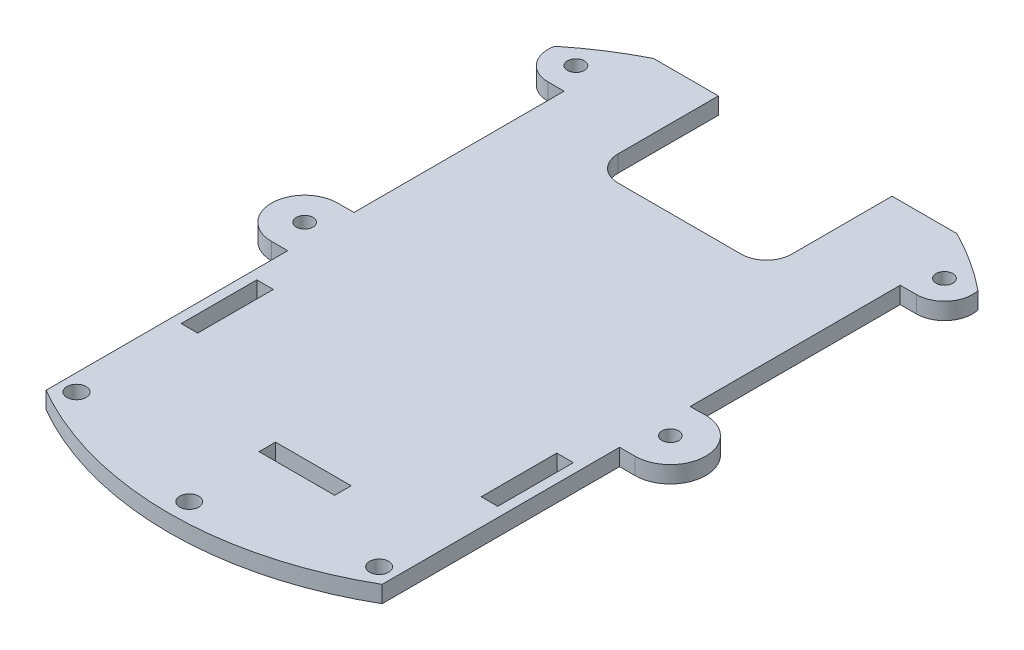
SolidWorks part; units mm, degrees
ref_plane "Alzado" through (0, 0, 0) normal (0, 0, 1) x (1, 0, 0)
ref_plane "Planta" through (0, 0, 0) normal (0, 1, 0) x (1, 0, 0)
ref_plane "Vista lateral" through (0, 0, 0) normal (1, 0, 0) x (0, 0, -1)
sketch "Croquis1" plane through (0, 0, 0) normal (0, 1, 0) x (1, 0, 0)
  line L0 (0, -45) -> (0, -62.5052) construction
  line L2 (-30, -38.4717) -> (-30, 4.6696)
  line L4 (30, -38.4717) -> (30, 3.903)
  line L5 (-30, -45) -> (30, 45) construction
  line L6 (-30, 45) -> (30, -45) construction
  line L8 (-27.0683, 67.0371) -> (-15.4924, 67.0371)
  line L9 (-32.892, 54) -> (-30, 54)
  line L10 (-30, 45) -> (-30, 54)
  line L11 (30, 45) -> (30, 54)
  line L12 (-32.892, 59) -> (-32.892, -85.621) construction
  line L13 (-15.4924, 55.619) -> (-15.4924, 67.0371)
  line L14 (15.5076, 55.6316) -> (15.5076, 67.0371)
  line L15 (15.5076, 67.0371) -> (27.0683, 67.0371)
  line L16 (-32.892, 10.5842) -> (-0.4332, 10.5842) construction
  line L17 (30, 54) -> (32.89, 54)
  line L18 (-0.4332, -33.1755) -> (-0.4332, 12.6245) construction
  line L19 (-10.9924, 44.6131) -> (11.0076, 44.6131)
  line L20 (15.5076, 49.1131) -> (15.5076, 55.6316)
  line L21 (-15.4924, 55.619) -> (-15.4924, 49.1131)
  line L22 (-32.892, 16.4988) -> (-30, 16.4988)
  line L23 (-32.892, 4.6696) -> (-30, 4.6696)
  line L24 (32.75, 10.2241) -> (0.4332, 10.5842) construction
  line L25 (32.75, 16.5451) -> (30, 16.4988)
  line L26 (32.75, 3.903) -> (30, 3.903)
  line L27 (-30, 16.4988) -> (-30, 45)
  line L28 (30, 16.4988) -> (30, 45)
  line L29 (-25.3, -2.597) -> (-28.25, -2.597)
  line L30 (25.3, -16.097) -> (28.25, -16.097)
  line L31 (25.3, -16.097) -> (25.3, -2.597)
  line L32 (25.3, -2.597) -> (28.25, -2.597)
  line L33 (28.25, -16.097) -> (28.25, -2.597)
  line L34 (25.3, -16.097) -> (28.25, -2.597) construction
  line L35 (25.3, -2.597) -> (28.25, -16.097) construction
  line L36 (-28.25, -16.097) -> (-28.25, -2.597)
  line L37 (-25.3, -16.097) -> (-28.25, -16.097)
  line L38 (-25.3, -16.097) -> (-25.3, -2.597)
  line L39 (12, -28.95) -> (-1.5, -28.95)
  line L40 (12, -28.95) -> (12, -26)
  line L41 (12, -26) -> (-1.5, -26)
  line L42 (-1.5, -28.95) -> (-1.5, -26)
  line L43 (12, -28.95) -> (-1.5, -26) construction
  line L44 (12, -26) -> (-1.5, -28.95) construction
  circle A0 centre (0, 13.4898) radius 60 construction
  arc A1 (-30, -38.4717) -> (30, -38.4717) centre (0, 13.4898) ccw
  arc A2 (-37.7667, 60.1125) -> (-32.892, 54) centre (-32.892, 59) ccw
  arc A3 (32.89, 54) -> (37.7642, 60.1145) centre (32.89, 59) ccw
  arc A4 (59.5975, 20.4278) -> (-59.5975, 20.4278) centre (0, 13.4898) ccw construction
  arc A5 (37.7642, 60.1145) -> (27.0683, 67.0371) centre (0, 13.4898) ccw
  arc A6 (-27.0683, 67.0371) -> (-37.7667, 60.1125) centre (0, 13.4898) ccw
  arc A7 (-32.892, 16.4988) -> (-32.892, 4.6696) centre (-32.892, 10.5842) ccw
  arc A8 (-15.4924, 49.1131) -> (-10.9924, 44.6131) centre (-10.9924, 49.1131) ccw
  arc A9 (11.0076, 44.6131) -> (15.5076, 49.1131) centre (11.0076, 49.1131) ccw
  arc A11 (32.75, 16.5451) -> (32.75, 3.903) centre (32.75, 10.2241) cw
  circle A12 centre (-32.892, 10.5842) radius 1.5
  circle A13 centre (32.75, 10.2241) radius 1.5
  circle A15 centre (-32.892, 59) radius 1.5
  circle A18 centre (32.89, 59) radius 1.5
  point P0 (0, 0)
  point P14 (5.25, -27.475)
  point P16 (0, 60.3484)
  point P22 (13.5, 48.6944)
  point P24 (13.5, 70.6944)
  point P27 (-13.5, 70.6944)
  point P28 (-13.5, 48.6944)
  point P30 (-15.5, 70.6944)
  point P38 (15.5, 70.6944)
  point P48 (-16.5916, 10.5842)
  point P52 (26.775, -9.347)
  point P55 (16.5916, 10.5842)
  dimension "D12" = 3
  dimension "D13" = 3
  dimension "D14" = 3
  dimension "D15" = 5
  dimension "D16" = 5
  dimension "D19" = 3
  dimension "D20" = 32.89
  dimension "D1" = 60
  dimension "D2" = 90
  dimension "D3" = 2.95
  dimension "D4" = 13.5
  dimension "D5" = 60
  dimension "D6" = 31
  dimension "D7" = 11.8292
  dimension "D8" = 30
  dimension "D9" = 1.75
  dimension "D10" = 42.3748
  dimension "D11" = 20
  dimension "D17" = 59
  dimension "D18" = 32.892
  dimension "D21" = 13.5
  dimension "D22" = 2.95
  dimension "D23" = 26
  dimension "D24" = 12
extrude "Saliente-Extruir1" add sketch "Croquis1" along normal blind 3
sketch "Croquis3" plane through (0, 3, 0) normal (0, 1, 0) x (1, 0, 0)
  line L2 (-29.6071, -34.52) -> (-29.8221, -34.8923)
  line L3 (29.8221, -34.8923) -> (29.6071, -34.52)
  line L4 (-29.6071, -34.52) -> (-29.8221, -34.8923)
  line L5 (29.8221, -34.8923) -> (29.6071, -34.52)
  circle A0 centre (0, 13.4898) radius 60
  circle A1 centre (-27.009, -36.02) radius 1.5
  circle A2 centre (27.009, -36.02) radius 1.5
  circle A3 centre (0, 13.4898) radius 56.3978
  circle A4 centre (0, -42.908) radius 1.5
  arc A9 (-33.2801, -36.2664) -> (-38, -47.2108) centre (-35, -42.0146) ccw
  arc A10 (-33.2801, -36.2664) -> (-29.8221, -34.8923) centre (-32.4201, -33.3923) ccw
  arc A11 (-25.8239, -33.264) -> (-29.6071, -34.52) centre (-27.009, -36.02) ccw
  arc A12 (-25.8239, -33.264) -> (25.8239, -33.264) centre (0, 23.6157) ccw
  arc A13 (29.6071, -34.52) -> (25.8239, -33.264) centre (27.009, -36.02) ccw
  arc A14 (29.8221, -34.8923) -> (33.2801, -36.2664) centre (32.4201, -33.3923) ccw
  arc A15 (38, -47.2108) -> (33.2801, -36.2664) centre (35, -42.0146) ccw
  arc A16 (-38, -47.2108) -> (38, -47.2108) centre (0, 18.6071) ccw
  arc A17 (-33.2801, -36.2664) -> (-38, -47.2108) centre (-35, -42.0146) ccw
  arc A18 (-33.2801, -36.2664) -> (-29.8221, -34.8923) centre (-32.4201, -33.3923) ccw
  arc A19 (-25.8239, -33.264) -> (-29.6071, -34.52) centre (-27.009, -36.02) ccw
  arc A20 (-25.8239, -33.264) -> (25.8239, -33.264) centre (0, 23.6157) ccw
  arc A21 (29.6071, -34.52) -> (25.8239, -33.264) centre (27.009, -36.02) ccw
  arc A22 (29.8221, -34.8923) -> (33.2801, -36.2664) centre (32.4201, -33.3923) ccw
  arc A23 (38, -47.2108) -> (33.2801, -36.2664) centre (35, -42.0146) ccw
  arc A24 (-38, -47.2108) -> (38, -47.2108) centre (0, 18.6071) ccw
  dimension "D2" = 3
  dimension "D3" = 3
  dimension "D4" = 3
  dimension "D1" = 0
hole_wizard "Taladro de margen para M31" positions "Croquis3D1" profile "Croquis4" hole size "M3" standard "Ansi Metric" end condition through all
sketch3d "Croquis3D1"
  point P0 (-27.009, 3, 36.02)
  point P3 (0, 3, 42.908)
  point P6 (27.009, 3, 36.02)
sketch "Croquis4" plane through (-27.009, 3, 36.02) normal (1, 0, 0) x (0, 0, 1)
  line L0 (0, 0) -> (0, 3)
  line L1 (0, 3) -> (1.7, 3)
  line L2 (1.7, 3) -> (1.7, 0)
  line L5 (1.7, 0) -> (0, 0)
  line L11 (0, -6.35) -> (0, 107.95) construction
  dimension "Diámetro de taladro hasta el siguiente" = 3.4
  dimension "Profundidad de taladro hasta el siguiente" = 3
